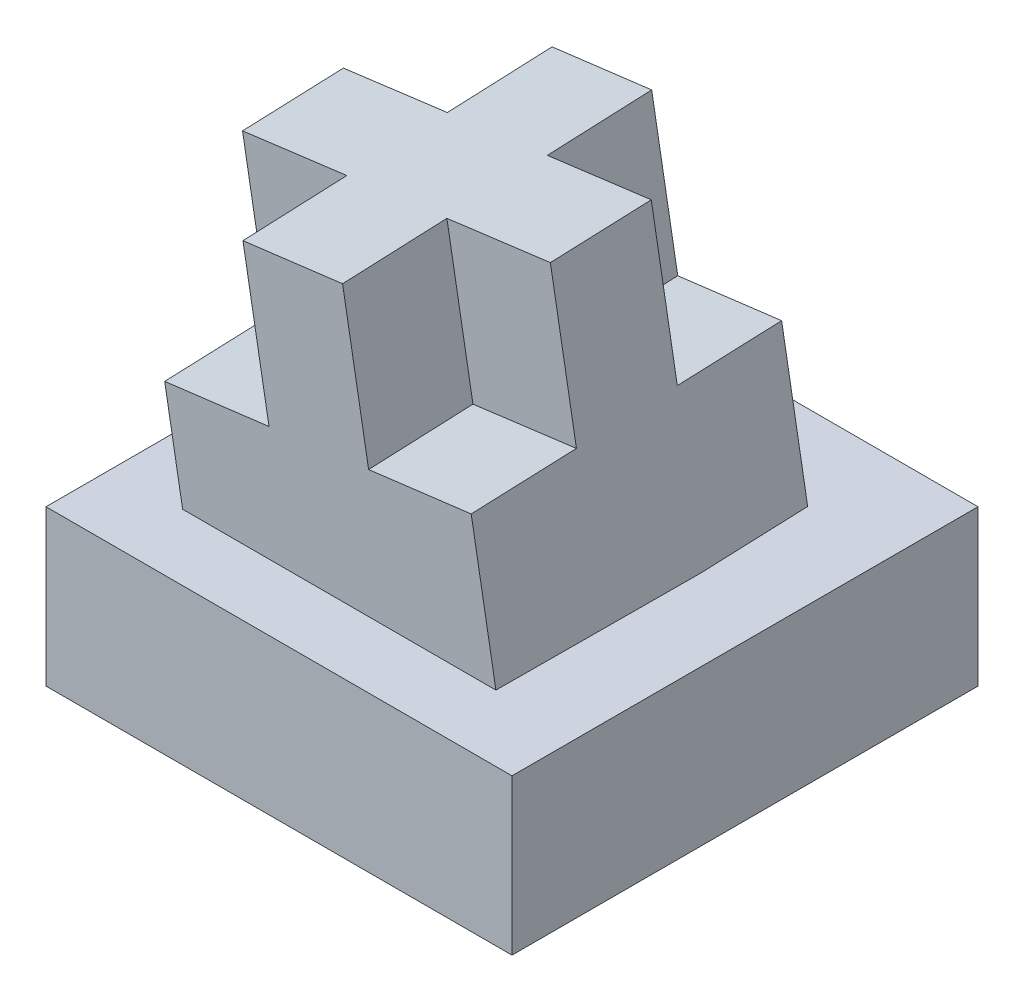
SolidWorks part; units mm, degrees
ref_plane "Front Plane" through (0, 0, 0) normal (0, 0, 1) x (1, 0, 0)
ref_plane "Top Plane" through (0, 0, 0) normal (0, 1, 0) x (1, 0, 0)
ref_plane "Right Plane" through (0, 0, 0) normal (1, 0, 0) x (0, 0, -1)
sketch "Sketch1" plane through (0, 0, 0) normal (0, 1, 0) x (1, 0, 0)
  line L1 (-15, -15) -> (15, -15)
  line L2 (-15, -15) -> (-15, 15)
  line L3 (-15, 15) -> (15, 15)
  line L4 (15, -15) -> (15, 15)
  line L5 (-15, -15) -> (15, 15) construction
  line L6 (-15, 15) -> (15, -15) construction
  point P0 (0, 0)
  dimension "D2" = 30
extrude "Boss-Extrude1" add sketch "Sketch1" along normal blind 10
sketch3d "3DSketch2"
  line L7 (15, 10, 15) -> (-15, 7.2698, 15) construction
  line L9 (-15, 7.2698, 15) -> (-15, 7.2698, -15) construction
  line L11 (-15, 7.2698, -15) -> (15, 10, 15)
  line L13 (-15, 10, 15) -> (15, 10, 15) construction
  line L14 (-15, 10, -15) -> (-15, 0, -15) construction
  line L15 (-15, 10, 15) -> (-15, 0, 15) construction
  line L16 (-15, 7.2698, -15) -> (-15, 6.0963, 15)
  line L17 (-15, 6.0963, 15) -> (-15, 7.2698, 15)
  line L18 (-15, 6.0963, 15) -> (15, 10, 15)
  dimension "D1" = 5.2
  dimension "D2" = 2.24
ref_plane "Plane2" through (-1.1032, 8.4784, 0.3316) normal (0.1289, -0.9909, -0.0388) x (-0.9917, -0.1288, -0.005)
sketch "Sketch2" plane through (-19.9967, 6.0237, 0.2356) normal (0.1289, -0.9909, -0.0388) x (-0.9917, -0.1288, -0.005)
  line L6 (-10.0189, -10.3421) -> (-30.0189, -10.3421)
  line L7 (-10.0189, -10.3421) -> (-10.0189, 9.6579)
  line L8 (-10.0189, 9.6579) -> (-30.0189, 9.6579)
  line L9 (-30.0189, -10.3421) -> (-30.0189, 9.6579)
  line L10 (-10.0189, -10.3421) -> (-30.0189, 9.6579) construction
  line L11 (-10.0189, 9.6579) -> (-30.0189, -10.3421) construction
  point P0 (-20.0189, -0.3421)
  dimension "D1" = 20
extrude "Boss-Extrude2" add sketch "Sketch2" against normal blind 20
sketch "Sketch5" plane through (-2.2921, 28.4771, 1.1079) normal (-0.1289, 0.9909, 0.0388) x (0.9916, 0.129, 0.0007)
  line L1 (-3.6728, -10.3324) -> (-3.6728, -3.6103)
  line L80 (9.5203, -10.3891) -> (-10.4795, -10.3032) construction
  line L85 (-3.6728, -3.6103) -> (-10.4508, -3.6103)
  line L86 (-10.4795, -10.3032) -> (-10.3936, 9.6966) construction
  line L91 (-10.4508, -3.6103) -> (-10.4795, -10.3032)
  line L92 (-10.4795, -10.3032) -> (-3.6728, -10.3324)
  line L103 (2.8272, -10.3603) -> (2.8272, -3.6102)
  line L104 (2.8272, -3.6102) -> (9.5494, -3.6102)
  line L105 (9.6062, 9.6108) -> (9.5203, -10.3891) construction
  line L106 (9.5494, -3.6102) -> (9.5203, -10.3891)
  line L107 (9.5203, -10.3891) -> (2.8272, -10.3603)
  line L108 (-10.3936, 9.6966) -> (-3.6728, 9.6678)
  line L109 (-10.3936, 9.6966) -> (9.6062, 9.6108) construction
  line L110 (-3.6728, 9.6678) -> (-3.6728, 2.8897)
  line L111 (-3.6728, 2.8897) -> (-10.4229, 2.8897)
  line L112 (-10.4229, 2.8897) -> (-10.3936, 9.6966)
  line L113 (9.6062, 9.6108) -> (9.5773, 2.8897)
  line L114 (9.5773, 2.8897) -> (2.8272, 2.8897)
  line L115 (2.8272, 2.8897) -> (2.8272, 9.6399)
  line L116 (2.8272, 9.6399) -> (9.6062, 9.6108)
  dimension "D1" = 6.5
  dimension "D2" = 6.5
  dimension "D3" = 6.5
  dimension "D4" = 6.5
extrude "Cut-Extrude3" cut sketch "Sketch5" against normal blind 10
